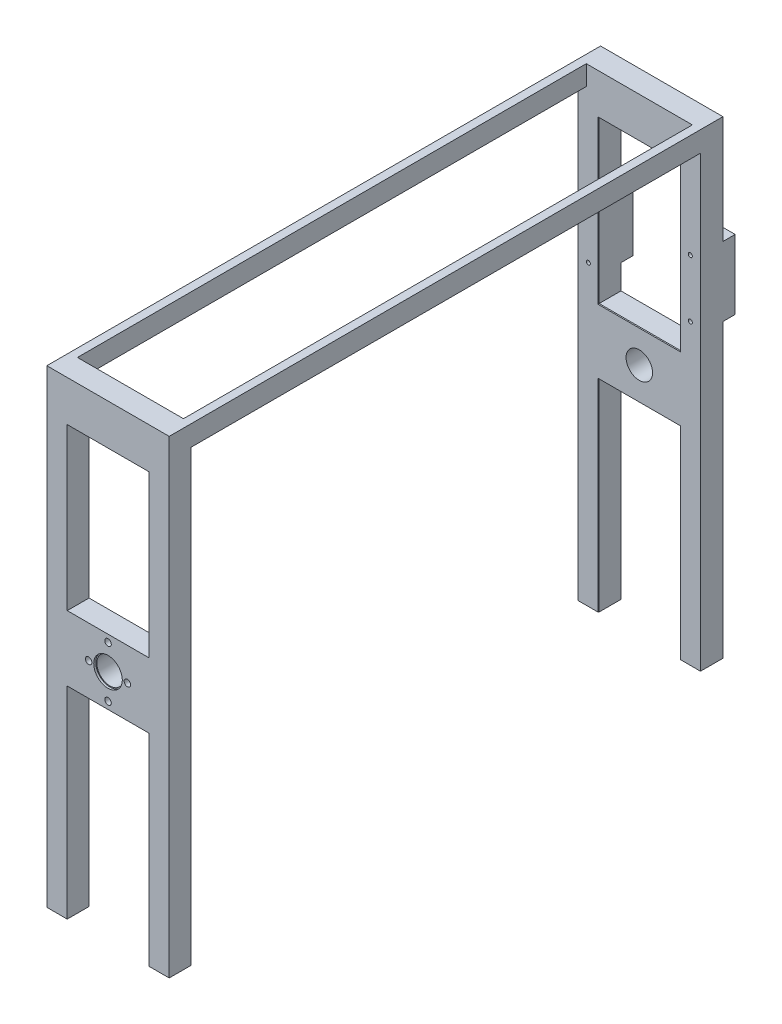
SolidWorks part; units mm, degrees
ref_plane "Front Plane" through (0, 0, 0) normal (0, 0, 1) x (1, 0, 0)
ref_plane "Top Plane" through (0, 0, 0) normal (0, 1, 0) x (1, 0, 0)
ref_plane "Right Plane" through (0, 0, 0) normal (1, 0, 0) x (0, 0, -1)
sketch "Sketch1" plane through (0, 0, 0) normal (0, 0, 1) x (1, 0, 0)
  line L1 (-30, -115) -> (30, -115)
  line L2 (-30, -115) -> (-30, 115)
  line L3 (-30, 115) -> (30, 115)
  line L4 (30, -115) -> (30, 115)
  line L5 (-30, -115) -> (30, 115) construction
  line L6 (-30, 115) -> (30, -115) construction
  point P0 (0, 0)
  dimension "D1" = 60
  dimension "D2" = 230
extrude "Boss-Extrude1" add sketch "Sketch1" along normal blind 11 from offset 8 offset against normal yes
sketch "Sketch2" plane through (0, 0, 0) normal (0, 0, 1) x (1, 0, 0)
  line L0 (30, -115) -> (30, 115) construction
  line L1 (-20, -16) -> (20, -16)
  line L2 (-20, -16) -> (-20, -115)
  line L3 (-20, -115) -> (20, -115)
  line L4 (20, -16) -> (20, -115)
  line L5 (-30, 115) -> (-30, -115) construction
  line L6 (-30, -115) -> (30, -115) construction
  dimension "D1" = 10
  dimension "D2" = 10
  dimension "D3" = 0
  dimension "D4" = 99
extrude "Cut-Extrude1" cut sketch "Sketch2" along normal through all both and the other way through all
sketch "Sketch3" plane through (0, 0, 0) normal (0, 0, 1) x (1, 0, 0)
  line L0 (30, -115) -> (30, 115) construction
  line L1 (-20, 16) -> (20, 16)
  line L2 (-20, 16) -> (-20, 95)
  line L3 (-20, 95) -> (20, 95)
  line L4 (20, 16) -> (20, 95)
  line L5 (-20, 16) -> (20, 95) construction
  line L6 (-20, 95) -> (20, 16) construction
  point P0 (0, 55.5)
  dimension "D1" = 40
  dimension "D2" = 10
  dimension "D3" = 16
  dimension "D4" = 79
extrude "Cut-Extrude2" cut sketch "Sketch3" along normal through all both and the other way through all
ref_plane "Plane16" through (0, 0, 252.5) normal (0, 0, 1) x (1, 0, 0)
sketch "Sketch4" plane through (0, 0, 252.5) normal (0, 0, 1) x (1, 0, 0)
  line L1 (-30, -115) -> (30, -115)
  line L2 (-30, -115) -> (-30, 115)
  line L3 (-30, 115) -> (30, 115)
  line L4 (30, -115) -> (30, 115)
  line L5 (-30, -115) -> (30, 115) construction
  line L6 (-30, 115) -> (30, -115) construction
  point P0 (0, 0)
  dimension "D1" = 60
  dimension "D2" = 230
extrude "Boss-Extrude3" add sketch "Sketch4" along normal blind 11 separate body
sketch "Sketch6" plane through (0, 0, 263.5) normal (0, 0, 1) x (1, 0, 0)
  line L1 (-20, 16) -> (20, 16)
  line L2 (-20, 16) -> (-20, 95)
  line L3 (-20, 95) -> (20, 95)
  line L4 (20, 16) -> (20, 95)
  line L5 (-20, 16) -> (20, 95) construction
  line L6 (-20, 95) -> (20, 16) construction
  line L7 (30, -115) -> (30, 115) construction
  point P0 (0, 55.5)
  dimension "D1" = 40
  dimension "D2" = 10
  dimension "D3" = 16
  dimension "D4" = 79
extrude "Cut-Extrude3" cut sketch "Sketch6" against normal through all both and the other way through all
sketch "Sketch7" plane through (0, 0, 252.5) normal (0, 0, 1) x (1, 0, 0)
  line L0 (-20, -16) -> (20, -16)
  line L1 (-20, -16) -> (-20, -115)
  line L2 (-20, -115) -> (20, -115)
  line L3 (20, -16) -> (20, -115)
  line L4 (30, -115) -> (30, 115) construction
  line L5 (-30, -115) -> (30, -115) construction
  dimension "D1" = 99
  dimension "D2" = 10
  dimension "D3" = 40
  dimension "D4" = 0
extrude "Cut-Extrude4" cut sketch "Sketch7" along normal through all both and the other way through all
sketch "Sketch8" plane through (0, 0, 3) normal (0, 0, 1) x (1, 0, 0)
  line L0 (-30, 115) -> (-30, -115) construction
  line L1 (-30, 105) -> (-26, 105)
  line L2 (-30, 105) -> (-30, 115)
  line L3 (-30, 115) -> (-26, 115)
  line L4 (-26, 105) -> (-26, 115)
  line L5 (0, -126.5) -> (0, 126.5) construction
  line L6 (26, 105) -> (26, 115)
  line L7 (30, 115) -> (26, 115)
  line L8 (30, 105) -> (30, 115)
  line L9 (30, 105) -> (26, 105)
  dimension "D1" = 4
  dimension "D2" = 10
  dimension "D3" = 105
extrude "Boss-Extrude4" add sketch "Sketch8" along direction (0, 0, -1) on the side of the normal up to surface (249.5 mm away)
sketch "Sketch9" plane through (0, 0, 252.5) normal (0, 0, 1) x (1, 0, 0)
  circle A0 centre (0, 0) radius 6.5
extrude "Cut-Extrude13" cut sketch "Sketch9" along normal through all both and the other way through all
sketch "Sketch13" plane through (0, 0, 252.5) normal (0, 0, -1) x (-1, 0, 0)
  circle A0 centre (0, 0) radius 7
extrude "Cut-Extrude15" cut sketch "Sketch13" against normal blind 1 from offset 10 offset against normal yes
sketch "Sketch14" plane through (0, 0, -8) normal (0, 0, -1) x (-1, 0, 0)
  circle A0 centre (0, 0) radius 7
extrude "Cut-Extrude16" cut sketch "Sketch14" against normal blind 1
sketch "Sketch15" plane through (0, 0, 263.5) normal (0, 0, 1) x (1, 0, 0)
  line L0 (0, -126.5) -> (0, 126.5) construction
  line L1 (33, 0) -> (-33, 0) construction
  circle A4 centre (9.5, 0) radius 1.6
  circle A5 centre (-9.5, 0) radius 1.6
  circle A6 centre (0, 12.5) radius 1.6
  circle A7 centre (0, -12.5) radius 1.6
  point P11 (0, 0)
extrude "Cut-Extrude17" cut sketch "Sketch15" against normal up to next
sketch "Sketch17" plane through (0, 0, -8) normal (0, 0, -1) x (-1, 0, 0)
  line L0 (0, 126.5) -> (0, -126.5) construction
  line L1 (20, 62) -> (30, 62)
  line L2 (20, 62) -> (20, 28)
  line L3 (20, 28) -> (30, 28)
  line L4 (30, 62) -> (30, 28)
  line L5 (20, 62) -> (30, 28) construction
  line L6 (20, 28) -> (30, 62) construction
  line L7 (-20, 28) -> (-30, 28)
  line L8 (-30, 62) -> (-30, 28)
  line L9 (-20, 62) -> (-30, 62)
  line L10 (-20, 62) -> (-20, 28)
  point P0 (25, 45)
  dimension "D1" = 45
  dimension "D2" = 25
  dimension "D3" = 10
  dimension "D4" = 34
extrude "Boss-Extrude5" add sketch "Sketch17" along normal blind 6
sketch "Sketch18" plane through (0, 0, -14) normal (0, 0, -1) x (-1, 0, 0)
  line L0 (-30, 28) -> (-20, 28) construction
  line L1 (-20, 62) -> (-30, 62) construction
  line L2 (-30, -115) -> (-30, 28) construction
  line L3 (-20, 16) -> (-20, 28) construction
  line L4 (0, 126.5) -> (0, -126.5) construction
  line L5 (-30, 28) -> (-20, 28) construction
  line L6 (20, 16) -> (-20, 16) construction
  circle A0 centre (-25, 59.2) radius 1
  circle A1 centre (-25, 31) radius 1
  circle A2 centre (25, 59.2) radius 1
  circle A3 centre (25, 31) radius 1
  dimension "D5" = 28.2
  dimension "D1" = 28
  dimension "D2" = 34
  dimension "D3" = 10
  dimension "D4" = 30
  dimension "D6" = 12
  dimension "D7" = 15
extrude "Cut-Extrude18" cut sketch "Sketch18" against normal up to next
chamfer "Chamfer1" distance 0.3 angle 45 1 edges at (-30, -5, 252.5)
chamfer "Chamfer2" distance 0.3 angle 45 1 edges at (30, -5, 252.5)
chamfer "Chamfer3" distance 0.3 angle 45 2 edges at (-26, 105, 127.75) (26, 105, 127.75)
chamfer "Chamfer4" distance 0.3 angle 45 7 edges at (0, 16, 3) (-20, 55.5, 3) (0, 95, 3) (20, 55.5, 3) (20, -65.5, 3) (0, -16, 3) (-20, -65.5, 3)
chamfer "Chamfer5" distance 0.3 angle 45 7 edges at (-20, -65.5, 252.5) (20, -65.5, 252.5) (0, -16, 252.5) (0, 95, 252.5) (-20, 55.5, 252.5) (0, 16, 252.5) (20, 55.5, 252.5)
